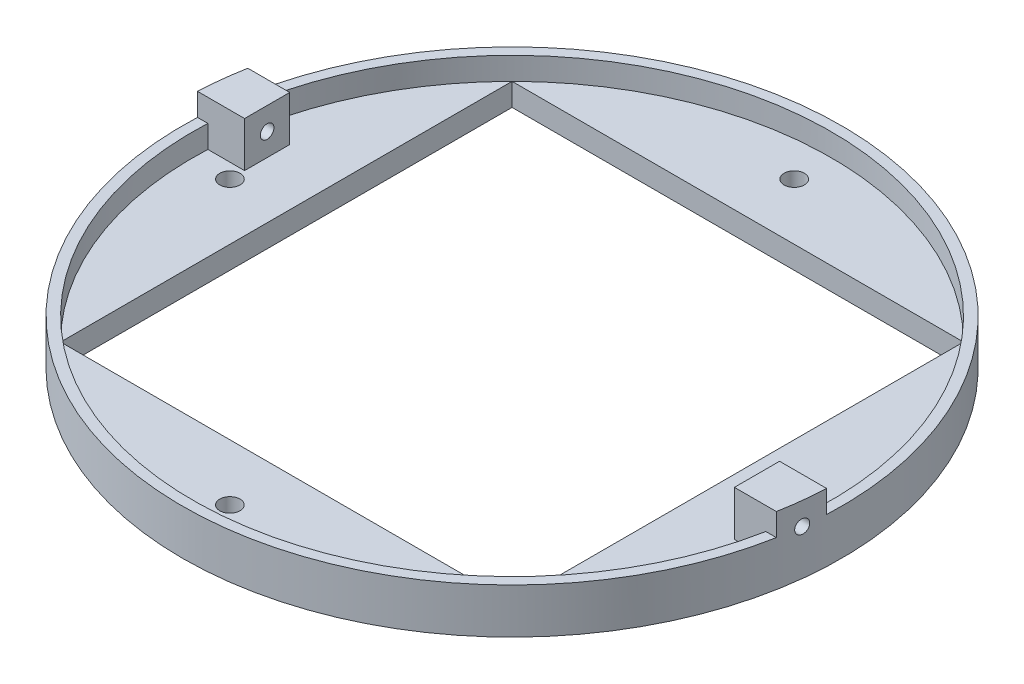
SolidWorks part; units mm, degrees
material "Custom Plastic"
ref_plane "Front Plane" through (0, 0, 0) normal (0, 0, 1) x (1, 0, 0)
ref_plane "Top Plane" through (0, 0, 0) normal (0, 1, 0) x (1, 0, 0)
ref_plane "Right Plane" through (0, 0, 0) normal (1, 0, 0) x (0, 0, -1)
sketch "Sketch1" plane through (0, 0, 0) normal (0, 1, 0) x (1, 0, 0)
  line L0 (0, 0) -> (0, -17.9724) construction
  line L1 (-50, -50) -> (50, -50)
  line L2 (-50, -50) -> (-50, 50)
  line L3 (-50, 50) -> (50, 50)
  line L4 (50, -50) -> (50, 50)
  line L5 (-50, -50) -> (50, 50) construction
  line L6 (-50, 50) -> (50, -50) construction
  line L7 (0, 0) -> (14.9739, 0) construction
  line L8 (0, 62.5) -> (14.3316, 62.5) construction
  line L9 (0, 76) -> (25.822, 76) construction
  circle A0 centre (0, 0) radius 76
  circle A1 centre (0, 0) radius 62.5 construction
  circle A2 centre (0, 62.5) radius 5
  circle A3 centre (62.5, 0) radius 5
  circle A4 centre (0, -62.5) radius 5
  circle A5 centre (-62.5, 0) radius 5
  dimension "D1" = 152
  dimension "D4" = 125
  dimension "D5" = 10
  dimension "D2" = 100
  dimension "D3" = 100
extrude "Boss-Extrude1" add sketch "Sketch1" along normal blind 5 contours A0 | L2 L1 L4 L3
sketch "Sketch2" plane through (0, 5, 0) normal (0, 1, 0) x (1, 0, 0)
  circle A0 centre (0, 0) radius 62.5 construction
  circle A1 centre (-62.5, 0) radius 2.25
  circle A2 centre (0, 62.5) radius 2.25
  circle A3 centre (62.5, 0) radius 2.25
  circle A4 centre (0, -62.5) radius 2.25
  dimension "D1" = 125
  dimension "D3" = 4.5
extrude "Cut-Extrude1" cut sketch "Sketch2" against normal blind 10
sketch "Sketch3" plane through (0, 5, 0) normal (0, 1, 0) x (1, 0, 0)
  circle A0 centre (0, 0) radius 70.7107
  circle A1 centre (0, 0) radius 76 construction
  circle A2 centre (0, 0) radius 76
  circle A3 centre (0, 0) radius 73
  dimension "D1" = 3
extrude "Boss-Extrude2" add sketch "Sketch3" along normal blind 5 contours A0 | A3
sketch "Sketch4" plane through (0, 5, 0) normal (0, 1, 0) x (1, 0, 0)
  circle A0 centre (0, 0) radius 73 construction
  circle A1 centre (0, 0) radius 76 construction
  circle A2 centre (0, 0) radius 73
  circle A3 centre (0, 0) radius 76
extrude "Cut-Extrude2" cut sketch "Sketch4" against normal blind 5
sketch "Sketch7" plane through (0, 5, 0) normal (0, 1, 0) x (1, 0, 0)
  line L0 (62.5, 2.25) -> (62.5, -2.25)
  line L1 (62.5, -2.25) -> (62.5, -3.25)
  line L2 (62.5, -3.25) -> (62.5, -13.25)
  line L3 (62.5, -3.25) -> (72.9276, -3.25)
  line L4 (62.5, -13.25) -> (71.7874, -13.25)
  line L5 (-62.5, -2.25) -> (-62.5, 2.25)
  line L6 (-62.5, 2.25) -> (-62.5, 3.25)
  line L7 (-62.5, 3.25) -> (-62.5, 13.25)
  line L8 (-62.5, 3.25) -> (-72.9276, 3.25)
  line L9 (-62.5, 13.25) -> (-71.7874, 13.25)
  circle A0 centre (62.5, 0) radius 2.25 construction
  circle A1 centre (0, 0) radius 73 construction
  circle A2 centre (0, 0) radius 73
  circle A3 centre (-62.5, 0) radius 2.25 construction
  dimension "D1" = 1
  dimension "D2" = 10
  dimension "D3" = 1
  dimension "D4" = 10
extrude "Boss-Extrude4" add sketch "Sketch7" along normal blind 10 contours L9 A2 L8 L7 | L4 A2 L3 L2
sketch "Sketch8" plane through (62.5, 0, 0) normal (-1, 0, 0) x (0, 0, 1)
  line L0 (8.25, 15) -> (8.25, 5)
  line L1 (3.25, 15) -> (13.25, 15) construction
  line L2 (3.25, 5) -> (13.25, 5) construction
  circle A0 centre (8.25, 10) radius 1.5
  dimension "D1" = 3
extrude "Cut-Extrude3" cut sketch "Sketch8" against normal blind 23 contours L0 A0 | L0 A0
sketch "Sketch9" plane through (-62.5, 0, 0) normal (1, 0, 0) x (0, 0, -1)
  line L0 (8.25, 15) -> (8.25, 5)
  line L1 (3.25, 15) -> (13.25, 15) construction
  line L2 (3.25, 5) -> (13.25, 5) construction
  circle A0 centre (8.25, 10) radius 1.5
  dimension "D1" = 3
extrude "Cut-Extrude4" cut sketch "Sketch9" against normal blind 21 contours L0 A0 | L0 A0
